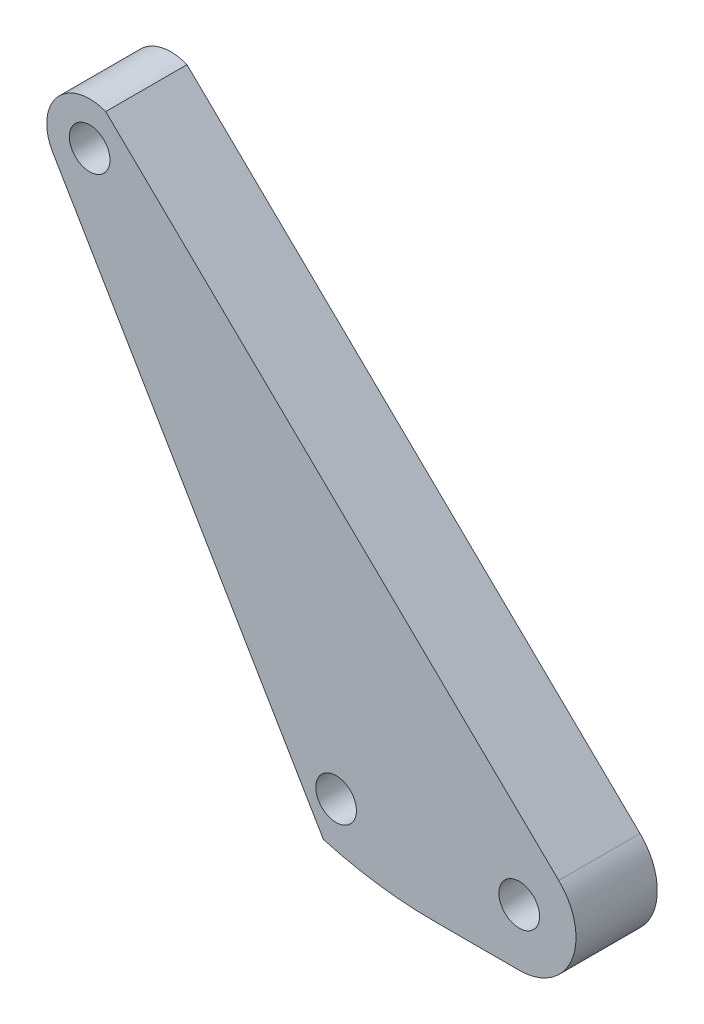
SolidWorks part; units mm, degrees
ref_plane "Front Plane" through (0, 0, 0) normal (0, 0, 1) x (1, 0, 0)
ref_plane "Top Plane" through (0, 0, 0) normal (0, 1, 0) x (1, 0, 0)
ref_plane "Right Plane" through (0, 0, 0) normal (1, 0, 0) x (0, 0, -1)
sketch "Sketch1" plane through (0, 0, 0) normal (0, 0, 1) x (1, 0, 0)
  line L1 (-17.978, 21.6366) -> (4.3147, 0.0202)
  line L2 (2.3694, -4.7805) -> (-1.8148, -4.7805)
  line L7 (-20.5866, 18.6043) -> (-7.2655, -4.0225)
  circle A1 centre (2.3694, -1.986) radius 1
  circle A2 centre (-18.7659, 19.6762) radius 1
  arc A3 (-17.978, 21.6366) -> (-20.5866, 18.6043) centre (-18.7659, 19.6762) ccw
  arc A4 (2.3694, -4.7805) -> (4.3147, 0.0202) centre (2.3694, -1.986) ccw
  arc A5 (-7.2655, -4.0225) -> (-1.8148, -4.7805) centre (-1.8148, 15.1963) ccw
  circle A7 centre (-6.6409, -1.986) radius 1
  dimension "D3" = 4
extrude "Boss-Extrude1" add sketch "Sketch1" along normal blind 4
